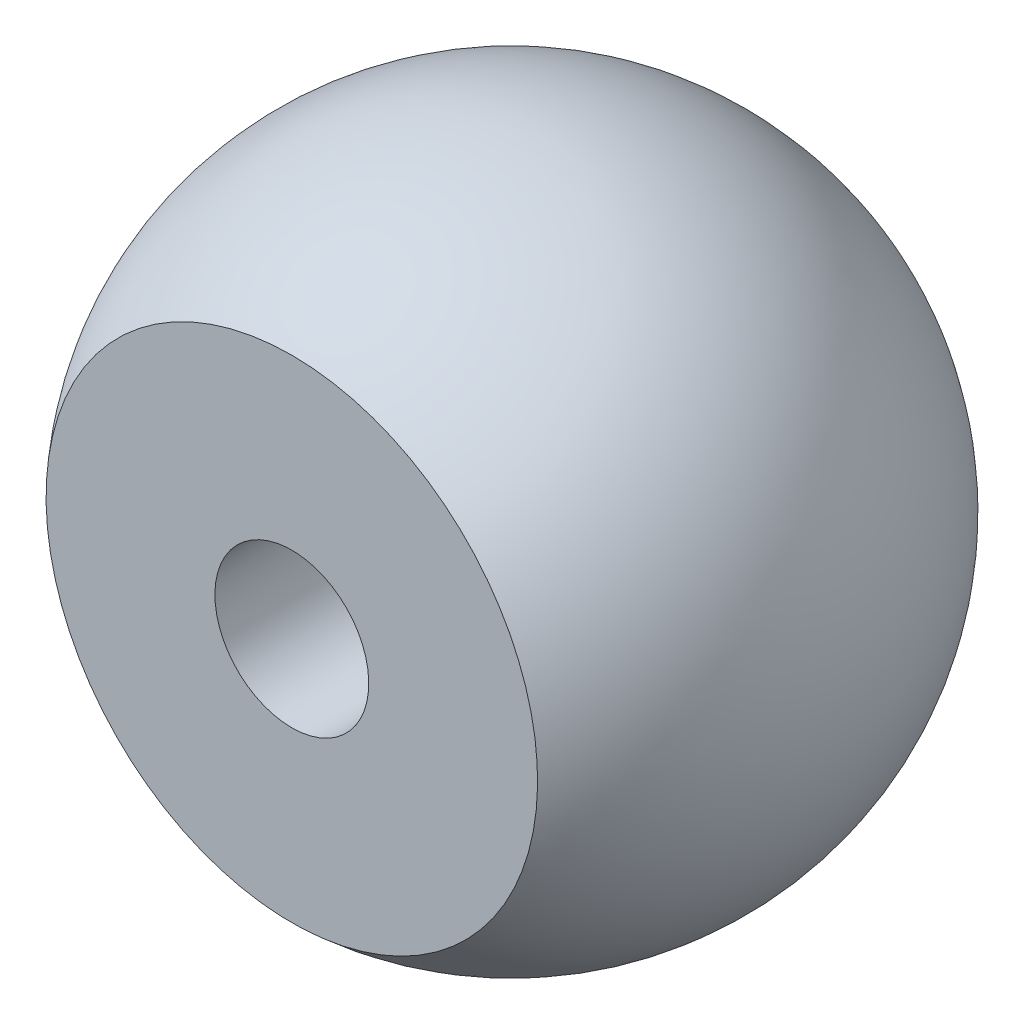
SolidWorks part; units mm, degrees
ref_plane "前视基准面" through (0, 0, 0) normal (0, 0, 1) x (1, 0, 0)
ref_plane "上视基准面" through (0, 0, 0) normal (0, 1, 0) x (1, 0, 0)
ref_plane "右视基准面" through (0, 0, 0) normal (1, 0, 0) x (0, 0, -1)
sketch "草图1" plane through (0, 0, 0) normal (1, 0, 0) x (0, 0, -1)
  line L0 (0, 9) -> (0, -9) construction
  line L1 (0, 9) -> (0, -9)
  arc A0 (0, 9) -> (0, -9) centre (0, 0) ccw
  dimension "D1" = 9
revolve "旋转1" add sketch "草图1" angle 360 about L0
sketch "草图2" plane through (0, 0, 0) normal (1, 0, 0) x (0, 0, -1)
  line L0 (-10.3921, 0) -> (0, 0) construction
  line L1 (-14.7843, 10.3866) -> (-6, 10.3866)
  line L2 (-14.7843, 10.3866) -> (-14.7843, -10.3866)
  line L3 (-14.7843, -10.3866) -> (-6, -10.3866)
  line L4 (-6, 10.3866) -> (-6, -10.3866)
  line L5 (-14.7843, 10.3866) -> (-6, -10.3866) construction
  line L6 (-14.7843, -10.3866) -> (-6, 10.3866) construction
  line L7 (0, 0) -> (9, 0) construction
  circle A0 centre (0, 0) radius 9 construction
  point P0 (-10.3921, 0)
  dimension "D1" = 15
  dimension "D2" = 8.7843
  dimension "D3" = 20.7732
extrude "切除-拉伸1" cut sketch "草图2" against normal through all both and the other way through all
hole_wizard "M5 螺纹孔1" positions "3D草图1" profile "草图4" tap size "M5" standard "GB"
sketch3d "3D草图1"
  circle A0 centre (0, 0, 6) radius 6.7082 construction
  point P0 (0, 0, 6)
  point P5 (0, 0, 12.7082)
sketch "草图4" plane through (0, 0, 6) normal (1, 0, 0) x (0, -1, 0)
  line L0 (0, 0) -> (0, 8.2618)
  line L1 (0, 8.2618) -> (2.1, 7)
  line L2 (2.1, 7) -> (2.1, 0)
  line L5 (2.1, 0) -> (0, 0)
  line L10 (0, 8.2618) -> (-2.1, 7) construction
  line L11 (0, -6.35) -> (0, 107.95) construction
  dimension "螺纹孔钻头直径" = 4.2
  dimension "螺纹孔钻头深度" = 7
  dimension "导头角度" = 118
cosmetic thread "孔螺蚊线1"
